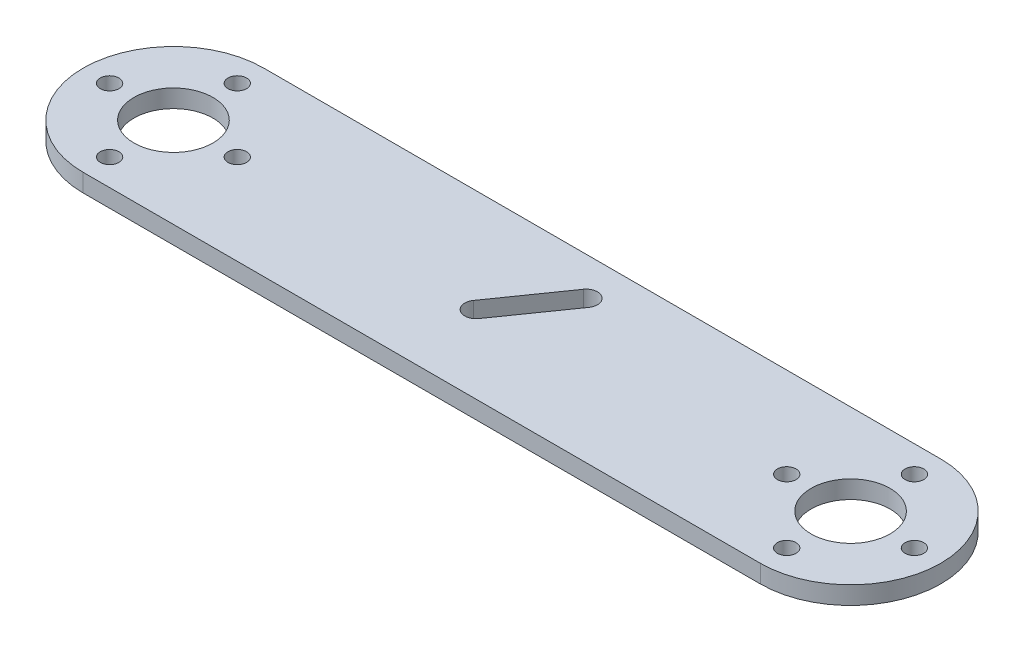
SolidWorks part; units mm, degrees
ref_plane "Front" through (0, 0, 0) normal (0, 0, 1) x (1, 0, 0)
ref_plane "Top" through (0, 0, 0) normal (0, 1, 0) x (1, 0, 0)
ref_plane "Right" through (0, 0, 0) normal (1, 0, 0) x (0, 0, -1)
sketch "Sketch1" plane through (0, 0, 0) normal (0, 1, 0) x (1, 0, 0)
  line L0 (68.6468, 32) -> (52.3903, 8.7833)
  line L1 (0, 0) -> (120, 0)
  line L2 (0, 0) -> (0, 32)
  line L3 (0, 32) -> (120, 32)
  line L4 (120, 0) -> (120, 32)
  line L5 (55.8776, 13.7637) -> (63.9076, 25.2318) construction
  line L6 (54.2393, 14.9108) -> (62.2693, 26.3789)
  line L7 (57.5159, 12.6165) -> (65.5459, 24.0846)
  arc A0 (0, 32) -> (0, 0) centre (0, 16) ccw
  arc A1 (120, 32) -> (120, 0) centre (120, 16) cw
  circle A2 centre (0, 16) radius 7
  circle A3 centre (120, 16) radius 7
  arc A4 (54.2393, 14.9108) -> (57.5159, 12.6165) centre (55.8776, 13.7637) ccw
  arc A5 (65.5459, 24.0846) -> (62.2693, 26.3789) centre (63.9076, 25.2318) ccw
  point P13 (59.8926, 19.4977)
  dimension "D3" = 14
  dimension "D1" = 32
  dimension "D2" = 120
extrude "Boss-Extrude1" add sketch "Sketch1" along normal blind 3.175 contours A3 L4 L3 L2 A2 L1 | A2 L2 A0 | A3 L4 A1
sketch "Sketch2" plane through (0, 3.175, 0) normal (0, 1, 0) x (1, 0, 0)
  line L0 (0, 16) -> (11.3137, 16)
  line L1 (60, 32) -> (60, 0)
  line L2 (0, 32) -> (120, 32) construction
  line L3 (0, 0) -> (120, 0) construction
  circle A0 centre (0, 16) radius 11.3137
  circle A1 centre (0, 27.3137) radius 1.65
  circle A2 centre (0, 4.6863) radius 1.65
  circle A3 centre (11.3137, 16) radius 1.65
  circle A4 centre (-11.3137, 16) radius 1.65
  circle A5 centre (120, 27.3137) radius 1.65
  circle A6 centre (131.3137, 16) radius 1.65
  circle A7 centre (120, 4.6863) radius 1.65
  circle A8 centre (108.6863, 16) radius 1.65
  point P25 (0, 0)
  dimension "D1" = 11.3137
extrude "Cut-Extrude1" cut sketch "Sketch2" against normal blind 10 contours A5 | A8 | A7 | A6 | A4 | A1 | A3 | A2
